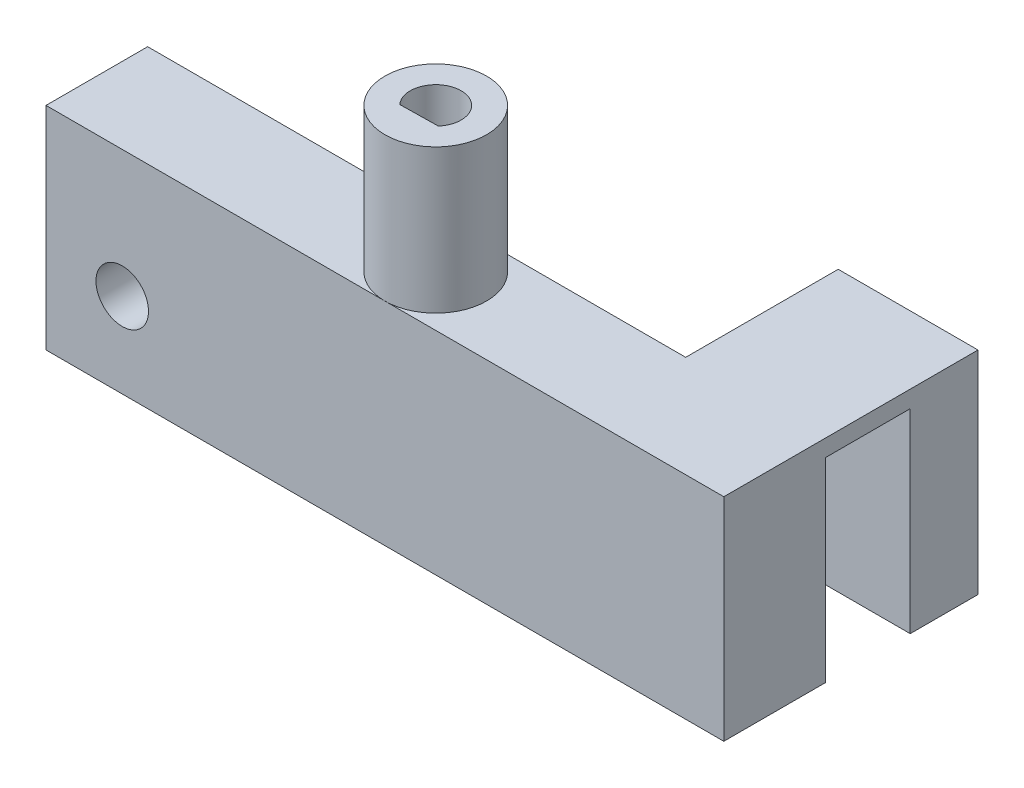
SolidWorks part; units mm, degrees
ref_plane "Front Plane" through (0, 0, 0) normal (0, 0, 1) x (1, 0, 0)
ref_plane "Top Plane" through (0, 0, 0) normal (0, 1, 0) x (1, 0, 0)
ref_plane "Right Plane" through (0, 0, 0) normal (1, 0, 0) x (0, 0, -1)
sketch "Sketch1" plane through (0, 0, 0) normal (0, 1, 0) x (1, 0, 0)
  circle A0 centre (0, 0) radius 3
  dimension "D1" = 6
extrude "Boss-Extrude1" add sketch "Sketch1" along normal blind 8.5
sketch "Sketch2" plane through (0, 8.5, 0) normal (0, 1, 0) x (1, 0, 0)
  line L0 (-1.1013, -1.0184) -> (1.1344, -0.9814)
  arc A0 (1.1344, -0.9814) -> (-1.1013, -1.0184) centre (0, 0) ccw
  dimension "D1" = 3
  dimension "D2" = 1
  dimension "D3" = 2.2358
extrude "Cut-Extrude1" cut sketch "Sketch2" against normal blind 6
sketch "Sketch3" plane through (0, 0, 0) normal (0, -1, 0) x (1, 0, 0)
  line L1 (-20, -3) -> (20, -3)
  line L2 (-20, -3) -> (-20, 3)
  line L3 (-20, 3) -> (20, 3)
  line L4 (20, -3) -> (20, 3)
  line L5 (-20, -3) -> (20, 3) construction
  line L6 (-20, 3) -> (20, -3) construction
  point P0 (0, 0)
  dimension "D1" = 6
  dimension "D2" = 40
extrude "Boss-Extrude2" add sketch "Sketch3" along normal blind 12.5
sketch "Sketch4" plane through (0, 0, -3) normal (0, 0, -1) x (-1, 0, 0)
  line L1 (20, -12.5) -> (-20, -12.5) construction
  circle A0 centre (15.5, -7.5) radius 1.55
  dimension "D2" = 3.1
  dimension "D1" = 15.5
  dimension "D3" = 5
extrude "Cut-Extrude2" cut sketch "Sketch4" against normal through all
sketch "Sketch6" plane through (0, 0, -3) normal (0, 0, -1) x (-1, 0, 0)
  line L0 (3.3, 0) -> (-3.3, 0) construction
  line L1 (-20, -12.5) -> (-11.75, -12.5)
  line L2 (-20, -12.5) -> (-20, 0)
  line L3 (-20, 0) -> (-11.75, 0)
  line L4 (-11.75, -12.5) -> (-11.75, 0)
  line L5 (20, -12.5) -> (20, 0) construction
  dimension "D1" = 31.75
extrude "Boss-Extrude3" add sketch "Sketch6" along normal blind 9
sketch "Sketch7" plane through (0, -12.5, 0) normal (0, -1, 0) x (1, 0, 0)
  line L0 (20, -12) -> (20, 3) construction
  line L1 (11.75, -3) -> (20, -3)
  line L2 (11.75, -3) -> (11.75, -8)
  line L3 (11.75, -8) -> (20, -8)
  line L4 (20, -3) -> (20, -8)
  dimension "D1" = 5
extrude "Cut-Extrude3" cut sketch "Sketch7" against normal blind 11.5
